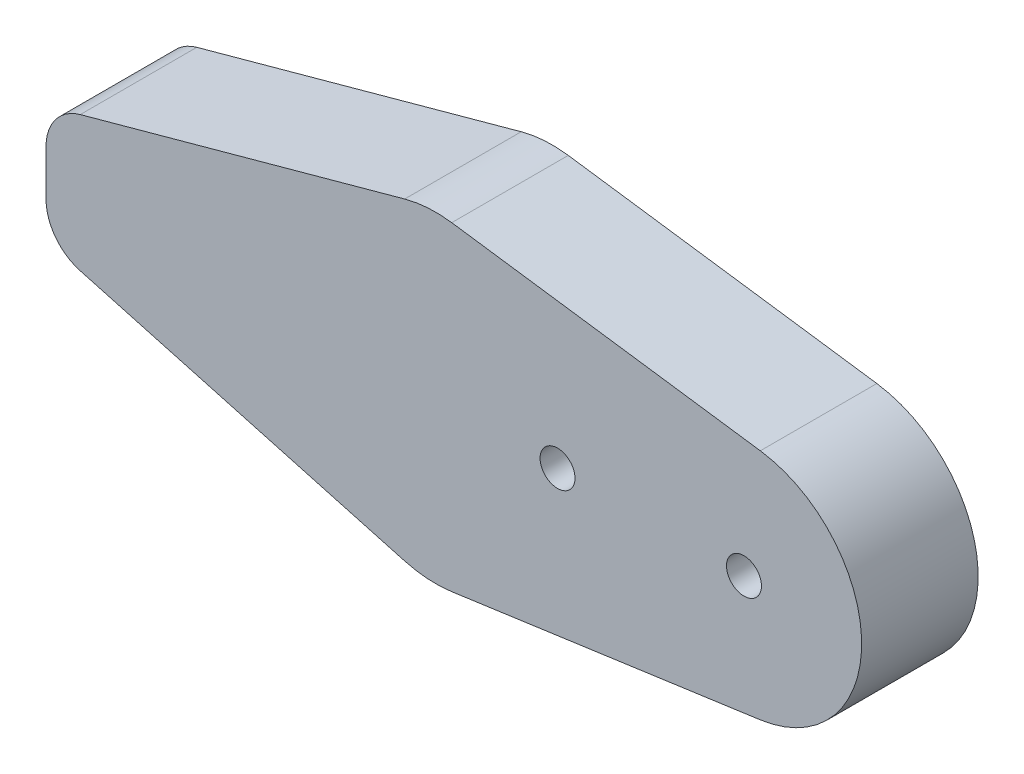
SolidWorks part; units mm, degrees
ref_plane "Front Plane" through (0, 0, 0) normal (0, 0, 1) x (1, 0, 0)
ref_plane "Top Plane" through (0, 0, 0) normal (0, 1, 0) x (1, 0, 0)
ref_plane "Right Plane" through (0, 0, 0) normal (1, 0, 0) x (0, 0, -1)
sketch "Sketch1" plane through (0, 0, 0) normal (0, 0, 1) x (1, 0, 0)
  line L0 (-26.097, 0) -> (32.0935, 0) construction
  line L1 (-11.359, -0.9752) -> (-11.359, 0.9752)
  line L2 (-9.8886, 2.9038) -> (4.0329, 6.7266)
  line L3 (6.0511, 6.8566) -> (19.2931, 5)
  line L4 (6.0511, -6.8566) -> (19.2931, -5)
  line L5 (-9.8886, -2.9038) -> (4.0329, -6.7266)
  arc A0 (19.2931, -5) -> (19.2931, 5) centre (18.5921, 0) ccw
  arc A1 (6.0511, -6.8566) -> (4.0329, -6.7266) centre (5.3568, -1.9051) cw
  arc A2 (4.0329, 6.7266) -> (6.0511, 6.8566) centre (5.3568, 1.9051) cw
  arc A3 (-9.8886, -2.9038) -> (-11.359, -0.9752) centre (-9.359, -0.9752) cw
  arc A4 (-11.359, 0.9752) -> (-9.8886, 2.9038) centre (-9.359, 0.9752) cw
  point P3 (23.641, 0)
  point P12 (-11.359, 0)
  point P14 (5.0286, -7)
  point P17 (5.0286, 7)
  point P20 (-11.359, -2.5)
  point P23 (-11.359, 2.5)
  dimension "D5" = 5
  dimension "D6" = 2
  dimension "D1" = 35
  dimension "D2" = 7
  dimension "D3" = 5
  dimension "D4" = 5
extrude "Boss-Extrude1" add sketch "Sketch1" along normal blind 5
sketch "Sketch2" plane through (-11.359, 0, 0) normal (-1, 0, 0) x (0, 0, 1)
  line L5 (1, -0.745) -> (1, 0.755)
  line L6 (1, 0.755) -> (3, 0.755)
  line L8 (3, -0.745) -> (1, -0.745)
  line L9 (0, 0.9752) -> (0, -0.9752) construction
  arc A1 (3, -0.745) -> (3, 0.755) centre (3, 0.005) ccw
  point P9 (0, 0)
  dimension "D1" = 1.5
  dimension "D2" = 2
  dimension "D3" = 1
  dimension "D4" = 0.755
extrude "Cut-Extrude2" cut sketch "Sketch2" against normal blind 16
sketch "Sketch3" plane through (0, 0, 5) normal (0, 0, 1) x (1, 0, 0)
  circle A0 centre (18.5921, 0) radius 0.75
  circle A1 centre (10.5921, 0) radius 0.75
  dimension "D1" = 1.5
  dimension "D2" = 1.5
  dimension "D3" = 8
extrude "Cut-Extrude3" cut sketch "Sketch3" against normal blind 8
